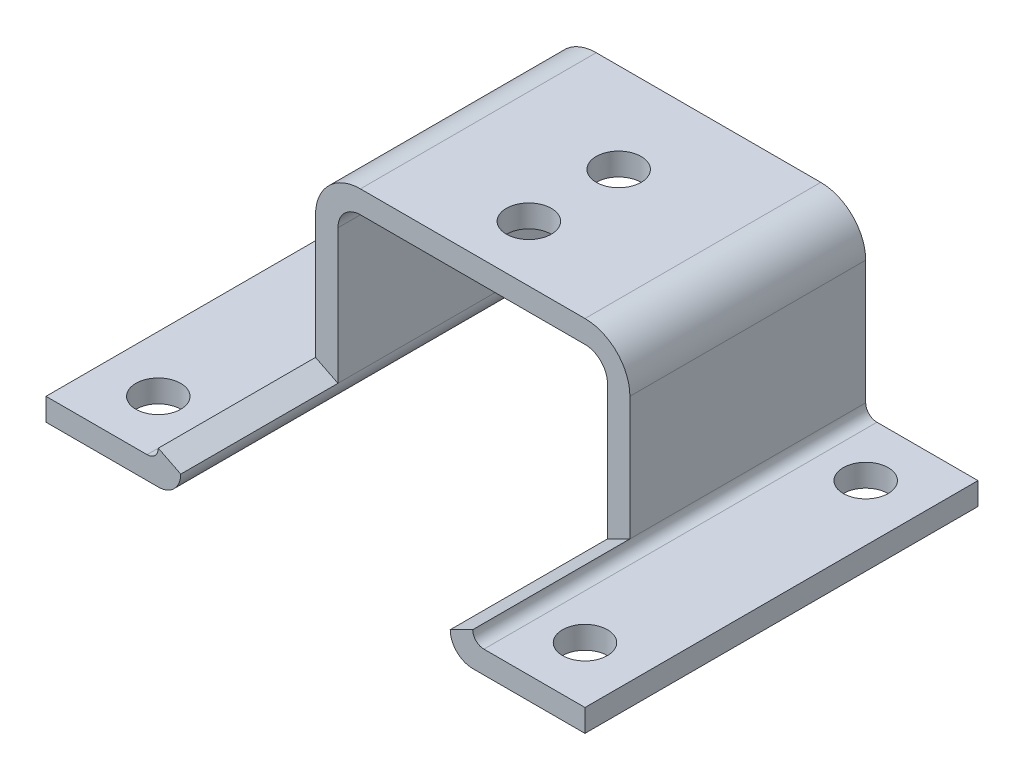
SolidWorks part; units mm, degrees
ref_plane "Front Plane" through (0, 0, 0) normal (0, 0, 1) x (1, 0, 0)
ref_plane "Top Plane" through (0, 0, 0) normal (0, 1, 0) x (1, 0, 0)
ref_plane "Right Plane" through (0, 0, 0) normal (1, 0, 0) x (0, 0, -1)
sketch "Sketch2" plane through (0, 0, 0) normal (0, 0, 1) x (1, 0, 0)
  line L0 (-24, 0) -> (-14, 0)
  line L1 (-12, 2) -> (-12, 14)
  line L2 (-10, 16) -> (0, 16)
  line L3 (0, 0) -> (0, 16) construction
  line L4 (-24, 2) -> (-15, 2)
  line L5 (-14, 3) -> (-14, 14)
  line L6 (-10, 18) -> (0, 18)
  line L7 (-24, 2) -> (-24, 0)
  line L8 (-14, 2) -> (-14, 14) construction
  line L9 (-24, 2) -> (-14, 2) construction
  line L10 (24, 2) -> (24, 0)
  line L11 (10, 18) -> (0, 18)
  line L12 (14, 3) -> (14, 14)
  line L13 (24, 2) -> (15, 2)
  line L14 (10, 16) -> (0, 16)
  line L15 (12, 2) -> (12, 14)
  line L16 (24, 0) -> (14, 0)
  line L17 (0, 18) -> (0, 32) construction
  arc A0 (-12, 14) -> (-10, 16) centre (-10, 14) cw
  arc A1 (-14, 0) -> (-12, 2) centre (-14, 2) ccw
  arc A2 (14, 3) -> (15, 2) centre (15, 3) ccw
  arc A3 (-14, 14) -> (-10, 18) centre (-10, 14) cw
  arc A4 (-14, 3) -> (-15, 2) centre (-15, 3) cw
  arc A5 (-14, 2) -> (-14, 2) centre (-14, 2) ccw construction
  arc A6 (14, 14) -> (10, 18) centre (10, 14) ccw
  arc A7 (14, 0) -> (12, 2) centre (14, 2) cw
  arc A8 (12, 14) -> (10, 16) centre (10, 14) ccw
  point P12 (-12, 16)
  point P15 (-12, 0)
  point P33 (12, 0)
  point P39 (12, 16)
  dimension "D4" = 2
  dimension "D6" = 1
  dimension "D1" = 16
  dimension "D2" = 12
  dimension "D3" = 24
  dimension "D5" = 2
extrude "Boss-Extrude1" add sketch "Sketch2" along normal blind 21
sketch "Sketch3" plane through (0, 0, 21) normal (0, 0, 1) x (1, 0, 0)
  line L0 (-14, 3) -> (-12, 2)
  line L1 (12, 2) -> (14, 3)
  line L12 (-24, 2) -> (-24, 0)
  line L13 (-24, 0) -> (-14, 0)
  line L14 (-12, 2) -> (-12, 14)
  line L15 (-10, 16) -> (10, 16)
  line L16 (12, 14) -> (12, 2)
  line L17 (14, 0) -> (24, 0)
  line L18 (24, 0) -> (24, 2)
  line L19 (24, 2) -> (15, 2)
  line L20 (14, 3) -> (14, 14)
  line L21 (10, 18) -> (-10, 18)
  line L22 (-14, 14) -> (-14, 3)
  line L23 (-15, 2) -> (-24, 2)
  line L24 (-24, 2) -> (-24, 0)
  line L25 (-24, 0) -> (-14, 0)
  line L29 (14, 0) -> (24, 0)
  line L30 (24, 0) -> (24, 2)
  line L31 (24, 2) -> (15, 2)
  line L35 (-15, 2) -> (-24, 2)
  arc A8 (-14, 0) -> (-12, 2) centre (-14, 2) ccw
  arc A9 (-10, 16) -> (-12, 14) centre (-10, 14) ccw
  arc A10 (12, 14) -> (10, 16) centre (10, 14) ccw
  arc A11 (12, 2) -> (14, 0) centre (14, 2) ccw
  arc A12 (14, 3) -> (15, 2) centre (15, 3) ccw
  arc A13 (14, 14) -> (10, 18) centre (10, 14) ccw
  arc A14 (-10, 18) -> (-14, 14) centre (-10, 14) ccw
  arc A15 (-15, 2) -> (-14, 3) centre (-15, 3) ccw
  arc A16 (-14, 0) -> (-12, 2) centre (-14, 2) ccw
  arc A19 (12, 2) -> (14, 0) centre (14, 2) ccw
  arc A20 (14, 3) -> (15, 2) centre (15, 3) ccw
  arc A23 (-15, 2) -> (-14, 3) centre (-15, 3) ccw
  dimension "D1" = 0
extrude "Boss-Extrude2" add sketch "Sketch3" along normal blind 14
sketch "Sketch4" plane through (0, 18, 0) normal (0, 1, 0) x (1, 0, 0)
  line L0 (0, 4.7474) -> (0, -25.1254) construction
sketch "Sketch6" plane through (0, 0, 0) normal (0, 1, 0) x (1, 0, 0)
  line L0 (-15, -35) -> (-24, -35) construction
  line L2 (0, 4.7474) -> (0, -25.1254) construction
  line L3 (10, -21) -> (-10, -21) construction
  line L4 (10, 0) -> (-10, 0) construction
  circle A0 centre (-19, -5) radius 2
  circle A1 centre (-19, -30) radius 2
  circle A2 centre (19, -30) radius 2
  circle A3 centre (19, -5) radius 2
  circle A4 centre (0, -8) radius 2
  circle A5 centre (0, -16) radius 2
  point P20 (0, 0)
  dimension "D1" = 25
  dimension "D4" = 8
  dimension "D2" = 5
  dimension "D3" = 38
  dimension "D5" = 5
extrude "Cut-Extrude6" cut sketch "Sketch6" along normal blind 5 contours A0 | A1 | A2 | A3
sketch "Sketch7" plane through (0, 18, 0) normal (0, 1, 0) x (1, 0, 0)
  circle A1 centre (0, -8) radius 2
  circle A2 centre (0, -8) radius 2
  circle A3 centre (19, -5) radius 2
  circle A4 centre (19, -5) radius 2
  circle A5 centre (19, -30) radius 2
  circle A6 centre (19, -30) radius 2
  circle A7 centre (-19, -30) radius 2
  circle A8 centre (-19, -30) radius 2
  circle A9 centre (-19, -5) radius 2
  circle A10 centre (-19, -5) radius 2
  circle A11 centre (0, -16) radius 2
  circle A12 centre (0, -16) radius 2
  dimension "D1" = 0
  dimension "D2" = 0
  dimension "D3" = 0
  dimension "D4" = 0
  dimension "D5" = 0
  dimension "D6" = 0
extrude "Cut-Extrude7" cut sketch "Sketch7" against normal blind 5 contours A2 | A12
